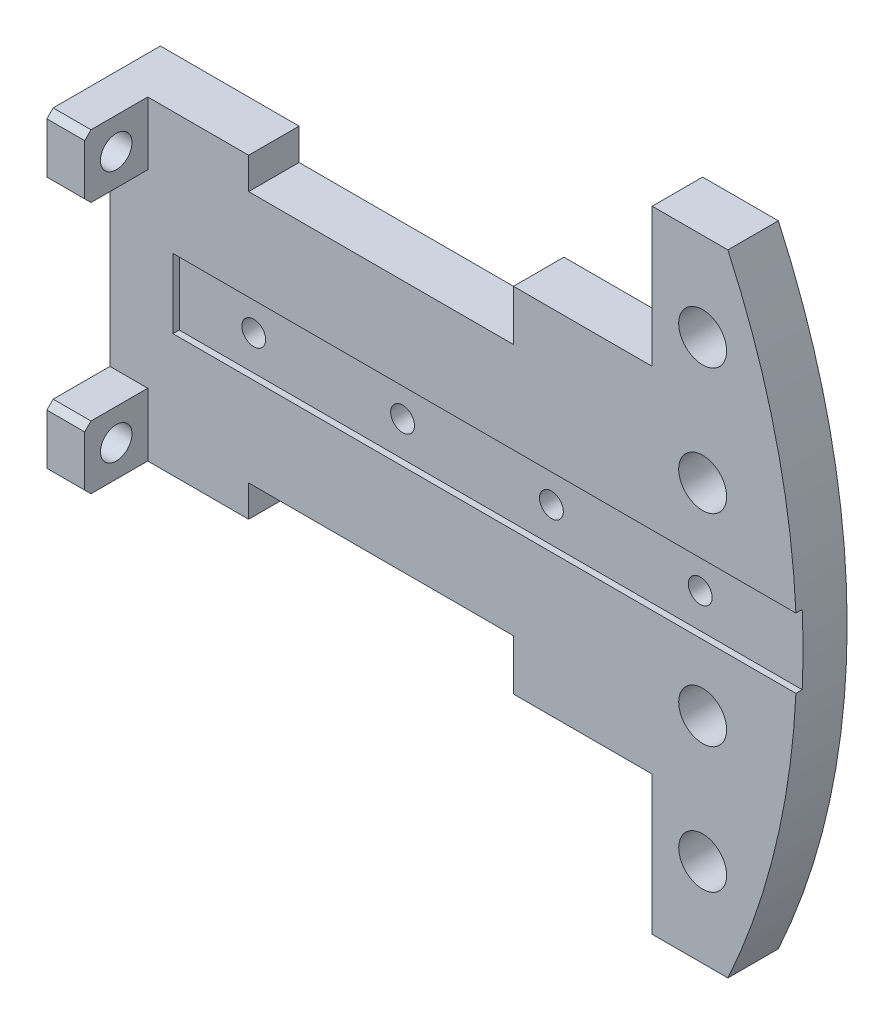
SolidWorks part; units mm, degrees
ref_plane "Front Plane" through (0, 0, 0) normal (0, 0, 1) x (1, 0, 0)
ref_plane "Top Plane" through (0, 0, 0) normal (0, 1, 0) x (1, 0, 0)
ref_plane "Right Plane" through (0, 0, 0) normal (1, 0, 0) x (0, 0, -1)
sketch "Sketch1" plane through (0, 0, 0) normal (0, 0, 1) x (1, 0, 0)
  line L0 (0, 0) -> (-149.3914, 0) construction
  line L1 (-35.3521, 31.75) -> (-42.9721, 31.75)
  line L2 (-42.9721, 31.75) -> (-42.9721, 17.78)
  line L3 (-42.9721, 17.78) -> (-56.9421, 17.78)
  line L4 (-56.9421, 17.78) -> (-56.9421, 12.7)
  line L5 (-56.9421, 12.7) -> (-83.6121, 12.7)
  line L6 (-83.6121, 12.7) -> (-83.6121, 15.875)
  line L7 (-83.6121, 15.875) -> (-97.5821, 15.875)
  line L8 (-97.5821, 15.875) -> (-97.5821, -15.875)
  line L9 (-83.6121, -15.875) -> (-97.5821, -15.875)
  line L10 (-83.6121, -12.7) -> (-83.6121, -15.875)
  line L11 (-56.9421, -12.7) -> (-83.6121, -12.7)
  line L12 (-56.9421, -17.78) -> (-56.9421, -12.7)
  line L13 (-42.9721, -17.78) -> (-56.9421, -17.78)
  line L14 (-42.9721, -31.75) -> (-42.9721, -17.78)
  line L15 (-35.3521, -31.75) -> (-42.9721, -31.75)
  arc A0 (-35.3521, 31.75) -> (-35.3521, -31.75) centre (-104.6224, 0) cw
  point P15 (-97.5821, 0)
  dimension "D1" = 13.97
  dimension "D7" = 76.2
  dimension "D2" = 25.4
  dimension "D3" = 35.56
  dimension "D4" = 7.62
  dimension "D5" = 13.97
  dimension "D6" = 31.75
  dimension "D8" = 54.61
  dimension "D9" = 63.5
extrude "Boss-Extrude1" add sketch "Sketch1" along normal blind 5.08
sketch "Sketch2" plane through (0, 0, 5.08) normal (0, 0, 1) x (1, 0, 0)
  line L0 (-97.5821, 0) -> (-52.7757, 0) construction
  line L1 (-97.5821, 15.875) -> (-97.5821, -15.875) construction
  line L2 (-91.2321, -3.5) -> (-91.2321, 3.5)
  line L3 (-91.2321, 3.5) -> (-27.7321, 3.5)
  line L4 (-27.7321, 3.5) -> (-27.7321, -3.5)
  line L5 (-91.2321, -3.5) -> (-27.7321, -3.5)
  point P10 (-27.7321, 0)
  point P11 (-91.2321, 0)
  dimension "D1" = 7
  dimension "D2" = 63.5
  dimension "D3" = 6.35
extrude "Cut-Extrude1" cut sketch "Sketch2" against normal blind 0.635
sketch "Sketch3" plane through (-97.5821, 0, 0) normal (-1, 0, 0) x (0, 0, 1)
  line L0 (0, 0) -> (16.8944, 0) construction
  line L1 (5.08, 15.875) -> (11.43, 15.875)
  line L2 (11.43, 15.875) -> (11.43, 9.525)
  line L3 (11.43, 9.525) -> (5.08, 9.525)
  line L4 (5.08, 15.875) -> (5.08, -15.875) construction
  line L5 (5.08, 9.525) -> (5.08, 15.875)
  circle A0 centre (8.255, 12.7) radius 1.5875
  dimension "D3" = 3.175
  dimension "D1" = 6.35
  dimension "D2" = 6.35
  dimension "D4" = 3.175
extrude "Boss-Extrude2" add sketch "Sketch3" against normal blind 3.81
chamfer "Chamfer1" distance 0.635 angle 45 2 edges at (-95.6771, 9.525, 11.43) (-95.6771, 15.875, 11.43)
mirror "Mirror1" about plane through (0, 0, 0) normal (0, 1, 0) of "Boss-Extrude2", "Chamfer1"
ref_plane "Plane1" through (-77.2621, 0, 0) normal (-1, 0, 0) x (0, 0, 1)
sketch "Sketch6" plane through (0, 0, 5.08) normal (0, 0, 1) x (1, 0, 0)
  line L0 (0, 0) -> (-61.5593, 0) construction
  line L1 (-37.8921, 31.5214) -> (-37.8921, -37.6463) construction
  line L3 (-35.3521, 31.75) -> (-42.9721, 31.75) construction
  line L4 (-42.9721, 31.75) -> (-42.9721, 17.78) construction
  circle A0 centre (-37.8921, 22.86) radius 2.413
  circle A1 centre (-37.8921, 10.16) radius 2.413
  circle A2 centre (-37.8921, -10.16) radius 2.413
  circle A3 centre (-37.8921, -22.86) radius 2.413
  dimension "D1" = 8.89
  dimension "D3" = 4.826
  dimension "D4" = 4.826
  dimension "D2" = 5.08
  dimension "D5" = 12.7
extrude "Cut-Extrude2" cut sketch "Sketch6" against normal through all
sketch "Sketch7" plane through (0, 0, 4.445) normal (0, 0, 1) x (1, 0, 0)
  line L0 (-91.2321, 0) -> (-22.6309, 0) construction
  line L1 (-91.2321, 3.5) -> (-91.2321, -3.5) construction
  line L2 (-91.2321, 3.5) -> (-91.2321, -3.5) construction
  circle A0 centre (-83.7315, 0) radius 1.2001
  circle A1 centre (-68.7455, 0) radius 1.2001
  circle A2 centre (-53.7595, 0) radius 1.2001
  circle A3 centre (-38.7735, 0) radius 1.2001
  dimension "D1" = 2.4003
  dimension "D2" = 7.5006
  dimension "D3" = 3
  dimension "D4" = 2
extrude "Cut-Extrude3" cut sketch "Sketch7" against normal through all
equation "\"D6@Sketch1\"=.625*2in"
